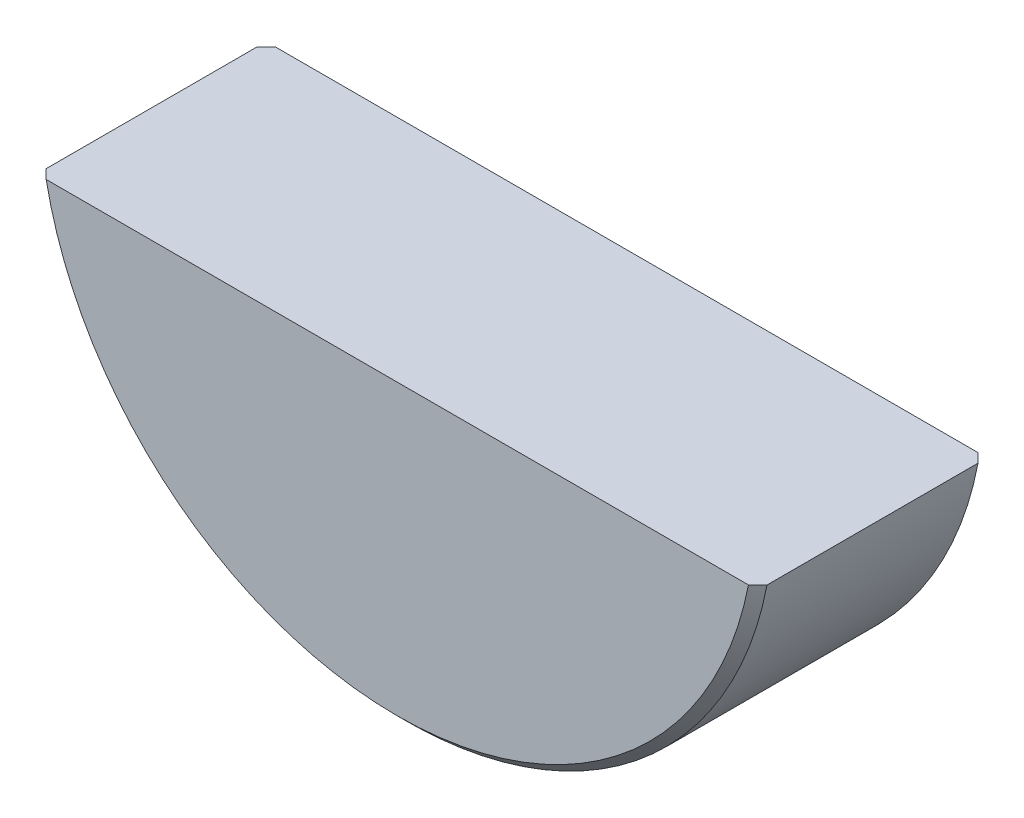
SolidWorks part; units mm, degrees
ref_plane "基准面1" through (0, 0, 0) normal (0, 0, 1) x (1, 0, 0)
ref_plane "基准面2" through (0, 0, 0) normal (0, 1, 0) x (1, 0, 0)
ref_plane "基准面3" through (0, 0, 0) normal (1, 0, 0) x (0, 0, -1)
sketch "尺寸草图" plane through (0, 0, 0) normal (0, 0, 1) x (1, 0, 0)
  line L0 (0, 0) -> (23.4, 0) construction
  point P3 (10, 0)
  point P4 (10, 0)
  point P5 (23, 0)
  point P6 (32, 0)
  point P7 (23, 0)
  dimension "b" = 10
  dimension "h" = 13
  dimension "C" = 0.4
  dimension "D" = 32
sketch "草图1" plane through (0, 0, 0) normal (0, 0, 1) x (1, 0, 0)
  line L0 (-15.7162, -3) -> (15.7162, -3)
  arc A0 (-15.7162, -3) -> (15.7162, -3) centre (0, 0) ccw
  dimension "D1" = 16
  dimension "D2" = 13
extrude "基体-拉伸" add sketch "草图1" along normal blind 10
chamfer "倒角1" distance 0.4 angle 45 2 edges at (0, -16, 0) (0, -16, 10)
